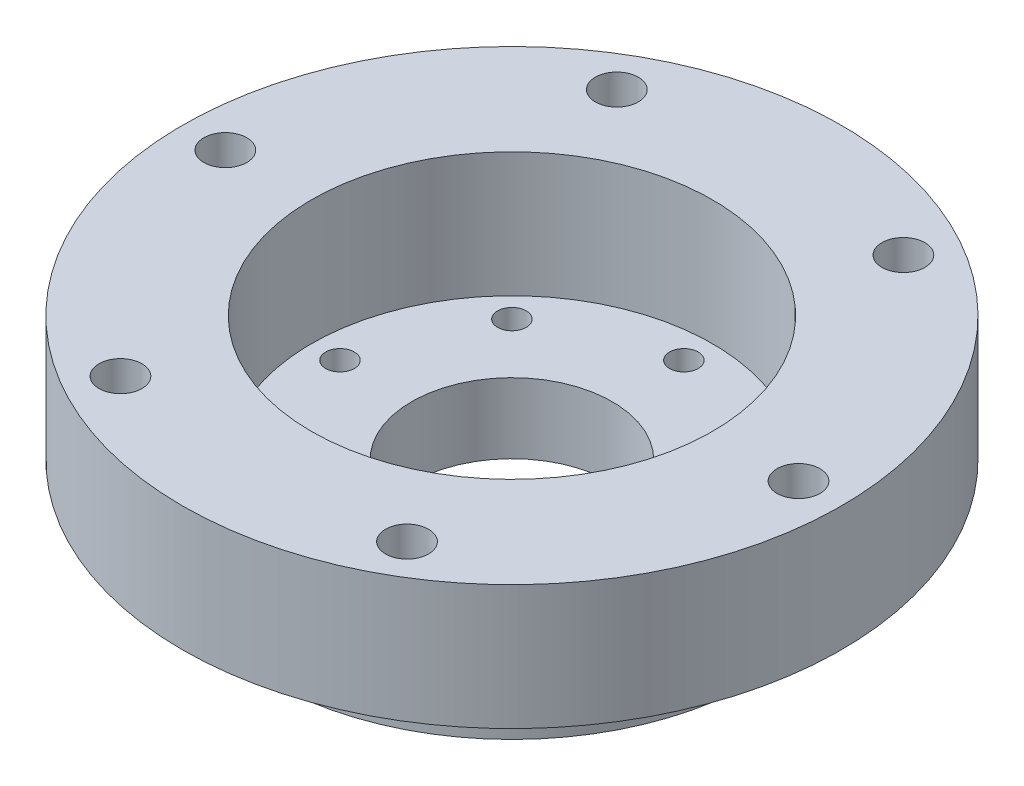
SolidWorks part; units mm, degrees
material "聚脂树脂"
ref_plane "前视基准面" through (0, 0, 0) normal (0, 0, 1) x (1, 0, 0)
ref_plane "上视基准面" through (0, 0, 0) normal (0, 1, 0) x (1, 0, 0)
ref_plane "右视基准面" through (0, 0, 0) normal (1, 0, 0) x (0, 0, -1)
other "Configuration Table"
sketch "草图1" plane through (0, 0, 0) normal (0, 1, 0) x (1, 0, 0)
  line L0 (0, 0) -> (0, 12.801) construction
  line L1 (0, 0) -> (13.0303, 0) construction
  line L2 (0, 0) -> (8.9558, 8.9558) construction
  circle A0 centre (0, 0) radius 17
  circle A2 centre (0, 0) radius 7
  circle A3 centre (0, 12) radius 1
  circle A4 centre (12, 0) radius 1
  circle A5 centre (0, -12) radius 1
  circle A6 centre (-12, 0) radius 1
  circle A7 centre (8.4853, 8.4853) radius 1
  circle A8 centre (8.4853, -8.4853) radius 1
  circle A9 centre (0, -12) radius 1
  circle A10 centre (-8.4853, -8.4853) radius 1
  circle A11 centre (-8.4853, 8.4853) radius 1
  dimension "D1" = 34
  dimension "D2" = 14
  dimension "D3" = 2
  dimension "D4" = 2
  dimension "D5" = 12
  dimension "D8" = 2
  dimension "D6" = 12
  dimension "D7" = 45
  dimension "D9" = 12
extrude "凸台-拉伸1" add sketch "草图1" along normal blind 4.9 contours A0 A8 A7 A5 A4 A3 A2 A6 A10 A11
sketch "草图2" plane through (0, 4.9, 0) normal (0, 1, 0) x (1, 0, 0)
  line L0 (0, 0) -> (24.658, 0) construction
  line L1 (0, 0) -> (0, 30.8703) construction
  line L2 (0, 0) -> (17.7456, 30.7363) construction
  circle A0 centre (0, 0) radius 23
  circle A8 centre (-12, 0) radius 1 construction
  circle A9 centre (-8.4853, -8.4853) radius 1 construction
  circle A10 centre (0, -12) radius 1 construction
  circle A11 centre (8.4853, -8.4853) radius 1 construction
  circle A12 centre (12, 0) radius 1 construction
  circle A13 centre (8.4853, 8.4853) radius 1 construction
  circle A14 centre (0, 12) radius 1 construction
  circle A15 centre (-8.4853, 8.4853) radius 1 construction
  circle A16 centre (0, 0) radius 7 construction
  circle A17 centre (-12, 0) radius 1
  circle A18 centre (-8.4853, -8.4853) radius 1
  circle A19 centre (0, -12) radius 1
  circle A20 centre (8.4853, -8.4853) radius 1
  circle A21 centre (12, 0) radius 1
  circle A22 centre (8.4853, 8.4853) radius 1
  circle A23 centre (0, 12) radius 1
  circle A24 centre (-8.4853, 8.4853) radius 1
  circle A25 centre (0, 0) radius 7
  circle A26 centre (20, 0) radius 1.5
  circle A28 centre (-20, 0) radius 1.5
  circle A32 centre (0, 0) radius 14
  circle A33 centre (10, 17.3205) radius 1.5
  circle A34 centre (-10, 17.3205) radius 1.5
  circle A35 centre (10, -17.3205) radius 1.5
  circle A36 centre (-10, -17.3205) radius 1.5
  circle M45 centre (0, 0) radius 17
  dimension "D1" = 30
  dimension "D2" = 3
  dimension "D3" = 3
  dimension "D4" = 20
  dimension "D5" = 28
  dimension "D6" = 46
  dimension "D7" = 20
extrude "凸台-拉伸2" add sketch "草图2" along normal blind 6 contours A0 A36 A34 A33 A26 A28 A35 M45 | A32 M45
sketch "草图3" plane through (0, 10.9, 0) normal (0, 1, 0) x (1, 0, 0)
  circle A10 centre (0, 0) radius 23 construction
  circle A11 centre (0, 0) radius 14 construction
  circle A12 centre (10, -17.3205) radius 1.5 construction
  circle A13 centre (20, 0) radius 1.5 construction
  circle A14 centre (10, 17.3205) radius 1.5 construction
  circle A15 centre (-10, -17.3205) radius 1.5 construction
  circle A16 centre (-20, 0) radius 1.5 construction
  circle A17 centre (-10, 17.3205) radius 1.5 construction
  circle A18 centre (0, 0) radius 23
  circle A19 centre (0, 0) radius 14
  circle A20 centre (10, -17.3205) radius 1.5
  circle A21 centre (20, 0) radius 1.5
  circle A22 centre (10, 17.3205) radius 1.5
  circle A23 centre (-10, -17.3205) radius 1.5
  circle A24 centre (-20, 0) radius 1.5
  circle A25 centre (-10, 17.3205) radius 1.5
extrude "凸台-拉伸3" add sketch "草图3" along normal blind 2.7
